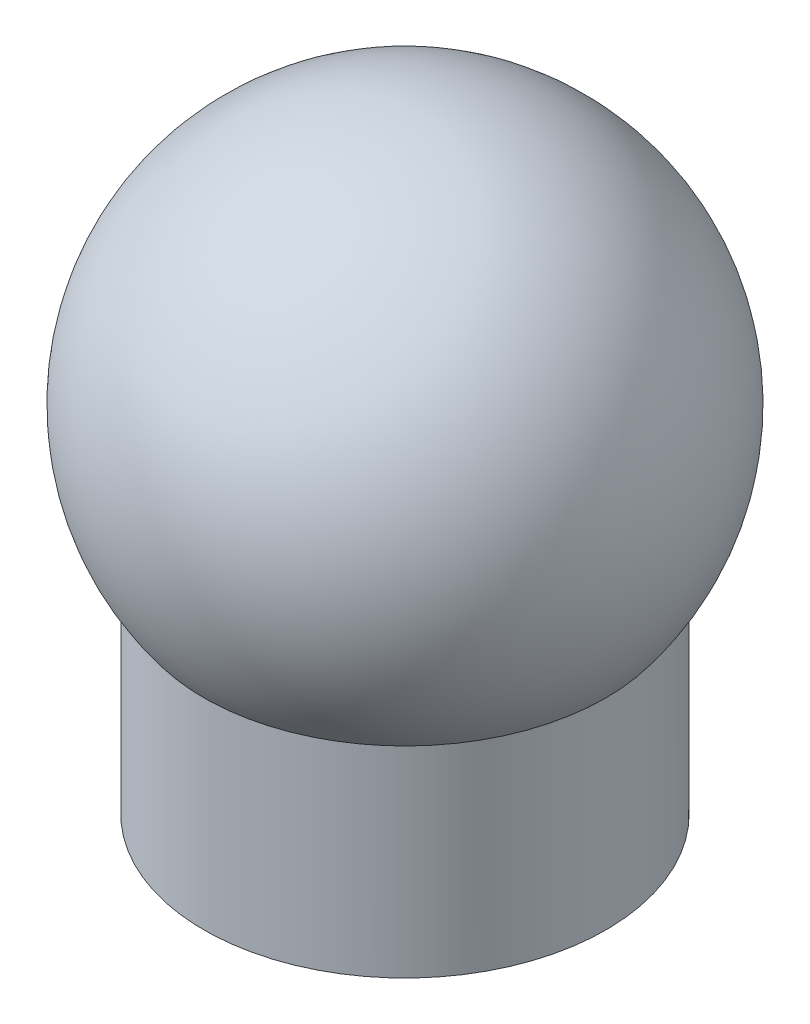
SolidWorks part; units mm, degrees
ref_plane "Front" through (0, 0, 0) normal (0, 0, 1) x (1, 0, 0)
ref_plane "Top" through (0, 0, 0) normal (0, 1, 0) x (1, 0, 0)
ref_plane "Right" through (0, 0, 0) normal (1, 0, 0) x (0, 0, -1)
sketch "Sketch1" plane through (0, 0, 0) normal (0, 0, 1) x (1, 0, 0)
  line L0 (0, 0) -> (0, 15.1328) construction
  line L1 (0, 0) -> (5, 0)
  line L2 (5, 0) -> (5, 5)
  line L3 (0, 0) -> (0, 15.1328)
  arc A0 (5, 5) -> (0, 15.1328) centre (0, 8.8328) ccw
  dimension "D3" = 6.3
  dimension "D1" = 5
  dimension "D2" = 10
revolve "Base-Revolve" add sketch "Sketch1" angle 360 about L0
